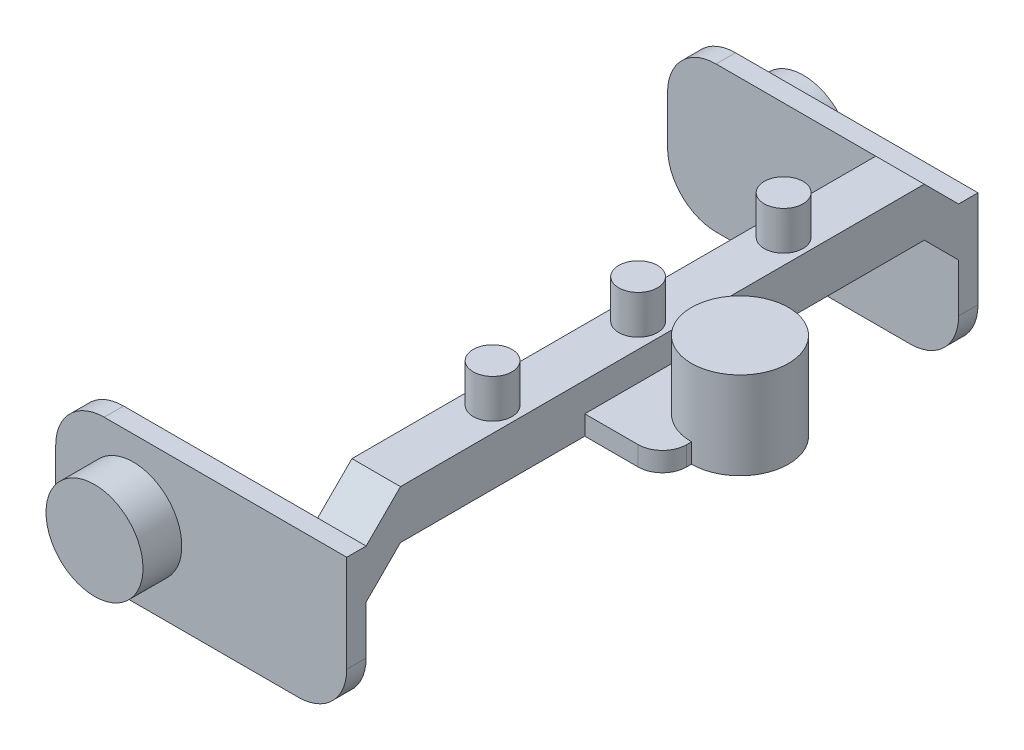
SolidWorks part; units mm, degrees
ref_plane "Front Plane" through (0, 0, 0) normal (0, 0, 1) x (1, 0, 0)
ref_plane "Top Plane" through (0, 0, 0) normal (0, 1, 0) x (1, 0, 0)
ref_plane "Right Plane" through (0, 0, 0) normal (1, 0, 0) x (0, 0, -1)
sketch "Sketch1" plane through (0, 0, 0) normal (0, 1, 0) x (1, 0, 0)
  line L1 (0, 27) -> (-5, 27)
  line L2 (0, 27) -> (0, -27)
  line L3 (0, -27) -> (-5, -27)
  line L4 (-5, 27) -> (-5, -27)
  dimension "D1" = 54
  dimension "D2" = 5
  dimension "D3" = 27
extrude "Boss-Extrude1" add sketch "Sketch1" along normal blind 5
sketch "Sketch3" plane through (0, 0, 0) normal (0, 1, 0) x (1, 0, 0)
  line L0 (0, -27) -> (0, 27) construction
  line L1 (0, -8) -> (16, -8)
  line L2 (0, -8) -> (0, 8)
  line L3 (0, 8) -> (16, 8)
  line L4 (16, -8) -> (16, 8)
  dimension "D1" = 16
  dimension "D2" = 16
  dimension "D3" = 8
extrude "Boss-Extrude2" add sketch "Sketch3" along normal blind 2
sketch "Sketch4" plane through (0, 2, 0) normal (0, 1, 0) x (1, 0, 0)
  circle A0 centre (8, 0) radius 5
  dimension "D1" = 10
extrude "Boss-Extrude3" add sketch "Sketch4" along normal blind 7
sketch "Sketch5" plane through (0, 0, 0) normal (1, 0, 0) x (0, 0, -1)
  line L0 (-27, 5) -> (-30.5355, 1.4645)
  dimension "D1" = 5
sketch "Sketch6" plane through (0, 0, 27) normal (0, 0, 1) x (1, 0, 0)
  line L1 (-5, 5) -> (0, 5)
  line L2 (-5, 5) -> (-5, 0)
  line L3 (-5, 0) -> (0, 0)
  line L4 (0, 5) -> (0, 0)
extrude "Boss-Extrude5" add sketch "Sketch6" along direction (0, -0.7071, 0.7071) on the side of the normal blind 5
mirror "Mirror1" about plane through (0, 0, 0) normal (0, 0, 1) of "Boss-Extrude5"
sketch "Sketch7" plane through (0, 5, 0) normal (0, 1, 0) x (1, 0, 0)
  circle A0 centre (-2.5, 0) radius 2
  circle A1 centre (-2.5, 15) radius 2
  circle A2 centre (-2.5, -15) radius 2
  dimension "D1" = 4
  dimension "D2" = 4
  dimension "D3" = 15
  dimension "D5" = 4
  dimension "D4" = 15
extrude "Boss-Extrude6" add sketch "Sketch7" along normal blind 4
sketch "Sketch10" plane through (0, 0, 30.5355) normal (0, 0, 1) x (1, 0, 0)
  line L1 (0, 1.4645) -> (-30, 1.4645)
  line L2 (0, 1.4645) -> (0, -13.5355)
  line L3 (0, -13.5355) -> (-30, -13.5355)
  line L4 (-30, 1.4645) -> (-30, -13.5355)
  dimension "D1" = 15
  dimension "D2" = 30
extrude "Boss-Extrude9" add sketch "Sketch10" along normal blind 2
sketch "Sketch11" plane through (0, 0, 32.5355) normal (0, 0, 1) x (1, 0, 0)
  line L0 (-30, 1.4645) -> (-30, -13.5355) construction
  circle A0 centre (-22, -6.0355) radius 5
  dimension "D1" = 10
  dimension "D2" = 8
extrude "Boss-Extrude10" add sketch "Sketch11" along normal blind 4
fillet "Fillet1" radius 5 3 edges at (-30, 1.4645, 31.5355) (-30, -13.5355, 31.5355) (0, -13.5355, 31.5355)
mirror "Mirror2" about plane through (0, 0, 0) normal (0, 0, 1) of "Fillet1", "Boss-Extrude9", "Boss-Extrude10"
sketch "Sketch12" plane through (0, 2, 0) normal (0, 1, 0) x (1, 0, 0)
  line L0 (8, 5) -> (8, 8)
  line L1 (16, 8) -> (0, 8) construction
  line L2 (8, 8) -> (16, 8)
  line L3 (16, 8) -> (16, -8)
  line L4 (16, -8) -> (8, -8)
  line L5 (0, -8) -> (16, -8) construction
  line L6 (8, -8) -> (8, -5)
  arc A0 (8, -5) -> (8, 5) centre (8, 0) ccw
  circle A1 centre (8, 0) radius 5 construction
extrude "Cut-Extrude1" cut sketch "Sketch12" against normal up to next
fillet "Fillet2" radius 2.5 2 edges at (8, 1, -8) (8, 1, 8)
